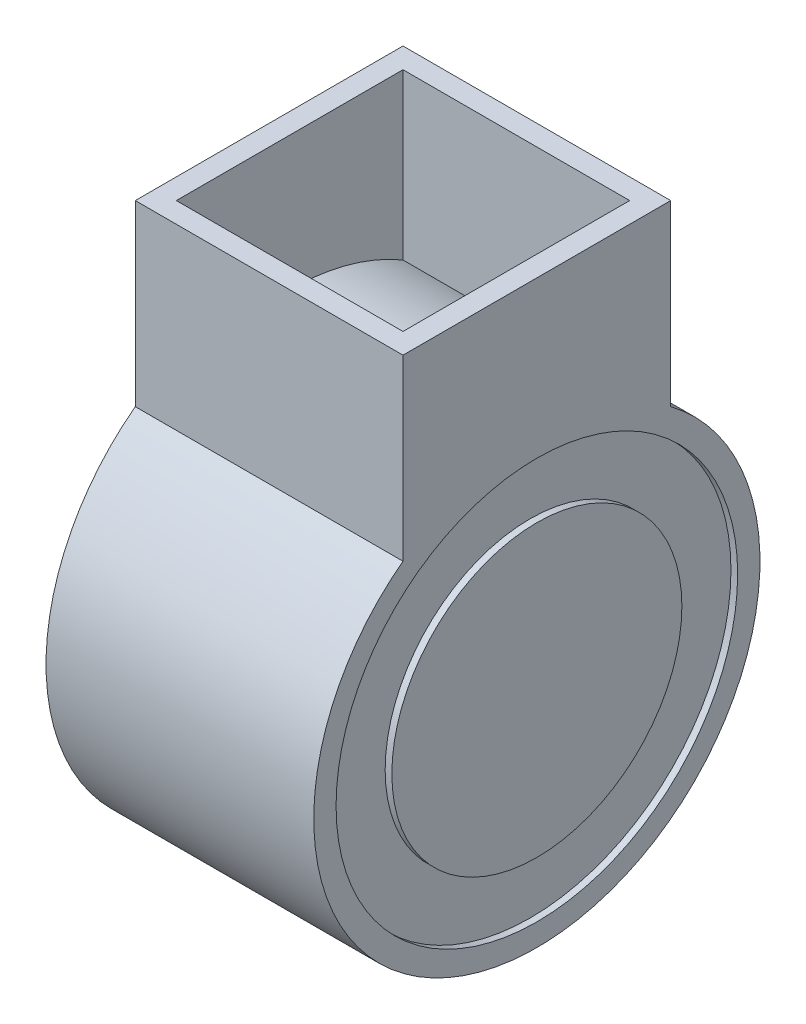
SolidWorks part; units mm, degrees
ref_plane "Alzado" through (0, 0, 0) normal (0, 0, 1) x (1, 0, 0)
ref_plane "Planta" through (0, 0, 0) normal (0, 1, 0) x (1, 0, 0)
ref_plane "Vista lateral" through (0, 0, 0) normal (1, 0, 0) x (0, 0, -1)
sketch "Croquis1" plane through (0, 0, 0) normal (1, 0, 0) x (0, 0, -1)
  circle A0 centre (0, 0) radius 50
  dimension "D1" = 100
extrude "Saliente-Extruir1" add sketch "Croquis1" along normal mid plane 60
ref_plane "Plano1" through (0, 80, 0) normal (0, 1, 0) x (1, 0, 0)
sketch "Croquis3" plane through (0, 80, 0) normal (0, 1, 0) x (1, 0, 0)
  line L1 (-30, -30) -> (30, -30)
  line L2 (-30, -30) -> (-30, 30)
  line L3 (-30, 30) -> (30, 30)
  line L4 (30, -30) -> (30, 30)
  line L5 (-30, -30) -> (30, 30) construction
  line L6 (-30, 30) -> (30, -30) construction
  line L7 (-25.4, -25.4) -> (25.4, -25.4)
  line L8 (-25.4, -25.4) -> (-25.4, 25.4)
  line L9 (-25.4, 25.4) -> (25.4, 25.4)
  line L10 (25.4, -25.4) -> (25.4, 25.4)
  line L11 (-25.4, -25.4) -> (25.4, 25.4) construction
  line L12 (-25.4, 25.4) -> (25.4, -25.4) construction
  point P0 (0, 0)
  point P6 (0, 0)
  dimension "D1" = 60
  dimension "D2" = 50.8
extrude "Saliente-Extruir2" add sketch "Croquis3" against normal up to next
sketch "Croquis4" plane through (30, 0, 0) normal (1, 0, 0) x (0, 0, -1)
  circle A0 centre (0, 0) radius 45
  circle A1 centre (0, 0) radius 32.5
  dimension "D1" = 90
  dimension "D2" = 65
extrude "Cortar-Extruir1" cut sketch "Croquis4" against normal blind 1.5
